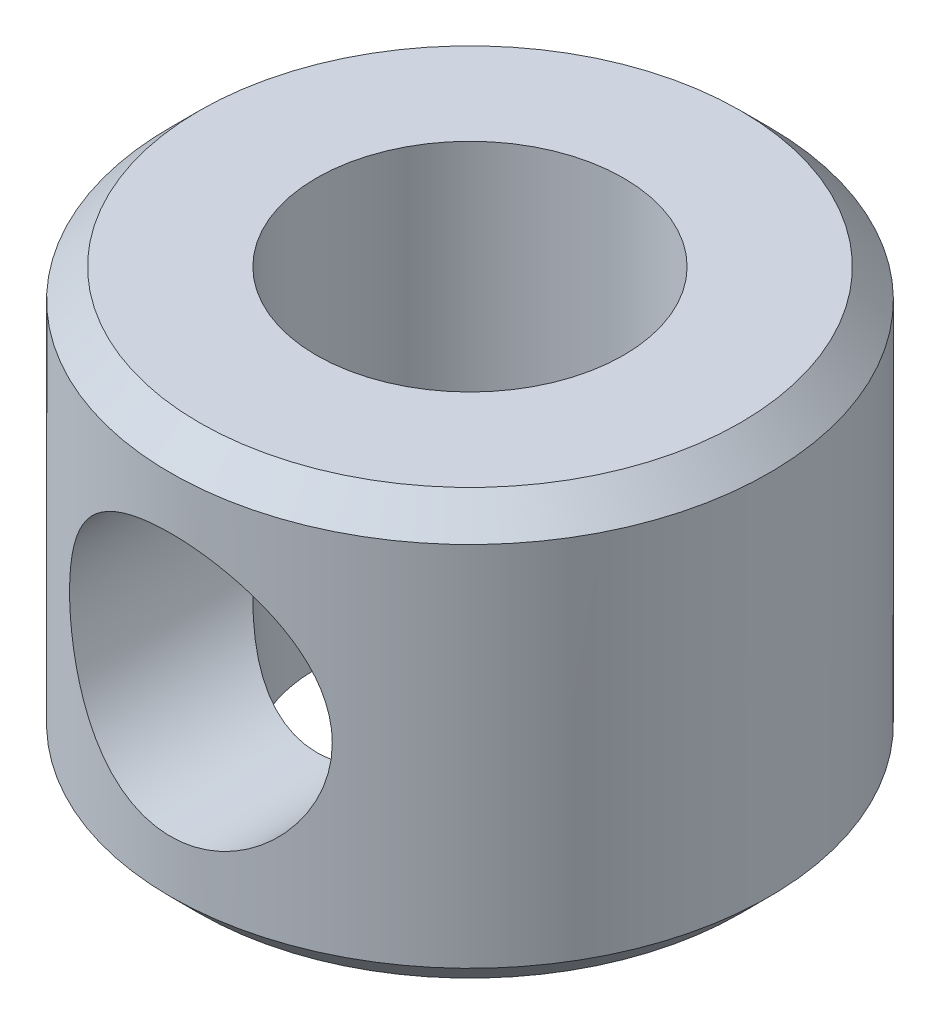
SolidWorks part; units mm, degrees
ref_plane "Front Plane" through (0, 0, 0) normal (0, 0, 1) x (1, 0, 0)
ref_plane "Top Plane" through (0, 0, 0) normal (0, 1, 0) x (1, 0, 0)
ref_plane "Right Plane" through (0, 0, 0) normal (1, 0, 0) x (0, 0, -1)
sketch "Sketch1" plane through (0, 0, 0) normal (0, 1, 0) x (1, 0, 0)
  circle A0 centre (0, 0) radius 3.937
  circle A1 centre (0, 0) radius 2.0193
  dimension "D1" = 7.874
  dimension "D2" = 4.0386
extrude "Boss-Extrude1" add sketch "Sketch1" along normal blind 5.588
ref_plane "Plane1" through (0, 0, 3.937) normal (0, 0, 1) x (1, 0, 0)
sketch "Sketch5" plane through (0, 0, 3.937) normal (0, 0, 1) x (1, 0, 0)
  line L0 (-3.937, 0) -> (3.937, 0) construction
  line L1 (3.937, 0) -> (3.937, 5.588) construction
  point P0 (0, 2.794)
  dimension "D1" = 2.794
  dimension "D2" = 3.937
hole_wizard "#8-32 Tapped Hole1" positions "3DSketch2" profile "Sketch6" tap size "#8-32" standard "ANSI Inch"
sketch3d "3DSketch2"
  point P0 (0, 2.794, 3.937)
sketch "Sketch6" plane through (0, 2.794, 3.937) normal (1, 0, 0) x (0, -1, 0)
  line L0 (0, 0) -> (0, 1.9177)
  line L1 (0, 1.9177) -> (1.7272, 1.9177)
  line L2 (1.7272, 1.9177) -> (1.7272, 0)
  line L5 (1.7272, 0) -> (0, 0)
  line L11 (0, -6.35) -> (0, 107.95) construction
  dimension "Thru Tap Drill Dia." = 3.4544
  dimension "Thru Tap Drill Depth" = 1.9177
cosmetic thread "Hole Thread1" parameters "D2"=4.1656
chamfer "Chamfer1" distance 0.381 angle 45 2 edges at (0, 0, 3.937) (0, 5.588, 3.937)
